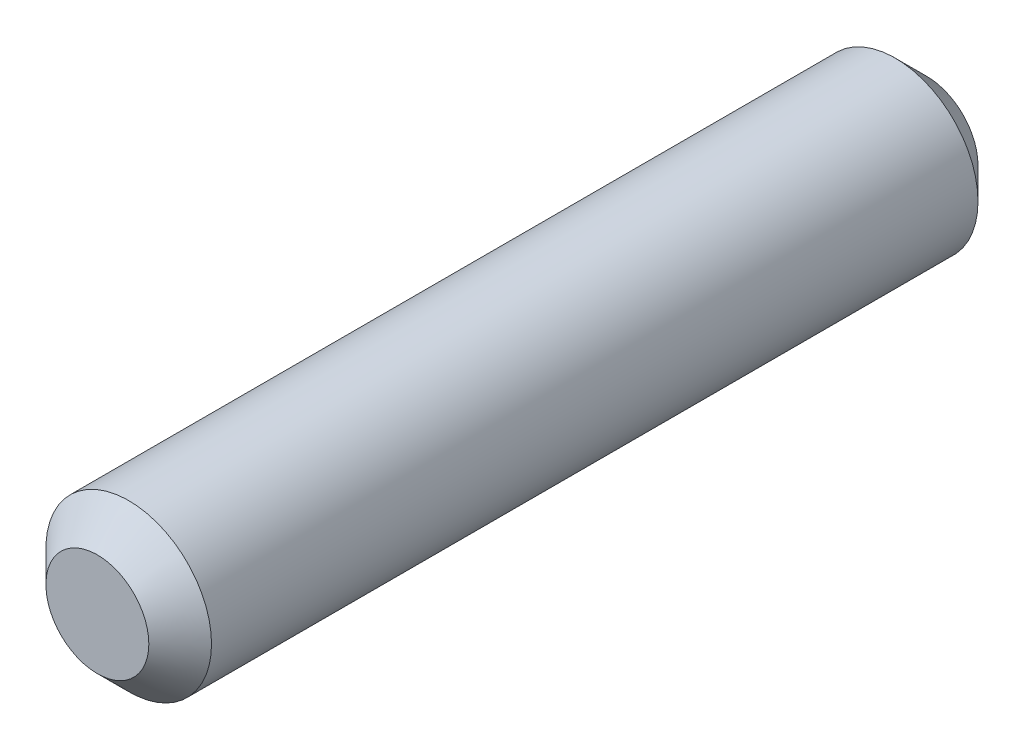
SolidWorks part; units mm, degrees
ref_plane "Front Plane" through (0, 0, 0) normal (0, 0, 1) x (1, 0, 0)
ref_plane "Top Plane" through (0, 0, 0) normal (0, 1, 0) x (1, 0, 0)
ref_plane "Right Plane" through (0, 0, 0) normal (1, 0, 0) x (0, 0, -1)
sketch "Sketch1" plane through (0, 0, 0) normal (0, 0, 1) x (1, 0, 0)
  circle A0 centre (0, 0) radius 1.585
  dimension "D1" = 3.17
extrude "Boss-Extrude1" add sketch "Sketch1" along normal blind 15.87
chamfer "Chamfer1" distance 0.6 angle 45 2 edges at (1.585, 0, 0) (1.585, 0, 15.87)
